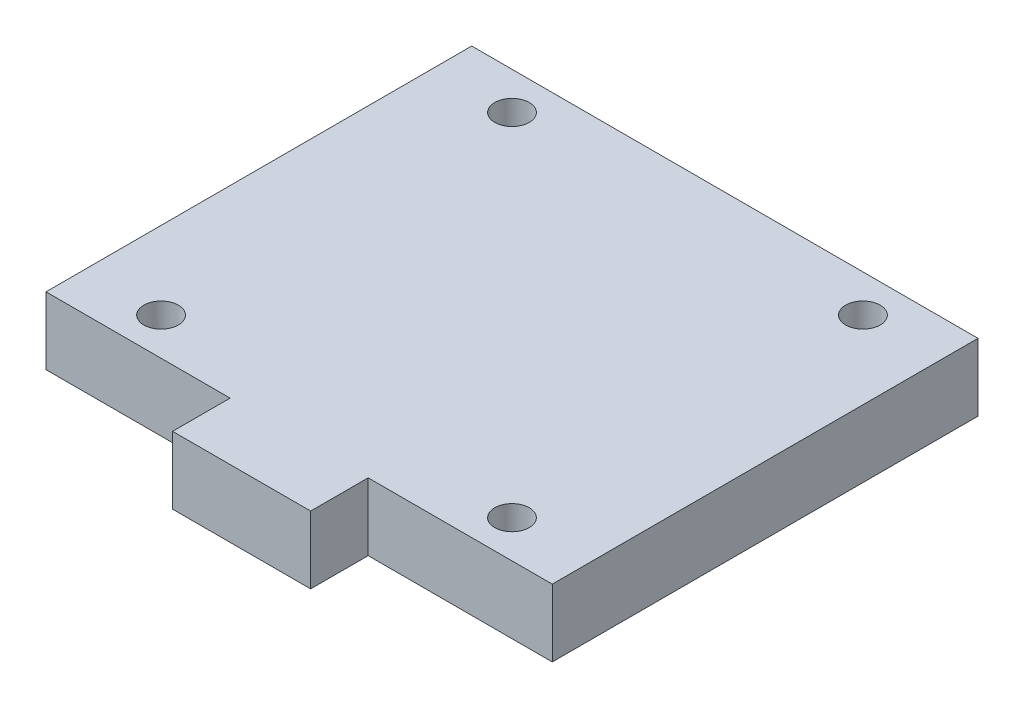
SolidWorks part; units mm, degrees
ref_plane "前视基准面" through (0, 0, 0) normal (0, 0, 1) x (1, 0, 0)
ref_plane "上视基准面" through (0, 0, 0) normal (0, 1, 0) x (1, 0, 0)
ref_plane "右视基准面" through (0, 0, 0) normal (1, 0, 0) x (0, 0, -1)
sketch "草图1" plane through (0, 0, 0) normal (0, 1, 0) x (1, 0, 0)
  line L1 (-15.25, 15.25) -> (15.25, 15.25) construction
  line L2 (-15.25, 15.25) -> (-15.25, -15.25) construction
  line L3 (-15.25, -15.25) -> (15.25, -15.25) construction
  line L4 (15.25, 15.25) -> (15.25, -15.25) construction
  line L5 (-15.25, 15.25) -> (15.25, -15.25) construction
  line L6 (-15.25, -15.25) -> (15.25, 15.25) construction
  line L11 (-22, -18.5) -> (22, -18.5)
  line L12 (-22, -18.5) -> (-22, 18.5)
  line L13 (-22, 18.5) -> (22, 18.5)
  line L14 (22, -18.5) -> (22, 18.5)
  line L15 (-22, -18.5) -> (22, 18.5) construction
  line L16 (-22, 18.5) -> (22, -18.5) construction
  line L17 (-6, -18.5) -> (6, -18.5)
  line L18 (-6, -18.5) -> (-6, -23.5)
  line L19 (-6, -23.5) -> (6, -23.5)
  line L20 (6, -18.5) -> (6, -23.5)
  circle A0 centre (-15.25, 15.25) radius 1.5
  circle A1 centre (15.25, 15.25) radius 1.5
  circle A2 centre (15.25, -15.25) radius 1.5
  circle A3 centre (-15.25, -15.25) radius 1.5
  point P0 (0, 0)
  point P10 (0, 0)
  point P19 (0, -18.5)
  point P20 (0, -18.5)
  dimension "D3" = 3
  dimension "D1" = 30.5
  dimension "D2" = 30.5
  dimension "D4" = 44
  dimension "D5" = 37
  dimension "D6" = 12
  dimension "D7" = 5
extrude "凸台-拉伸1" add sketch "草图1" along normal blind 5.86 contours L11 L14 L13 L12 A3 A2 A1 A0 | L20 L11 L18 L19
